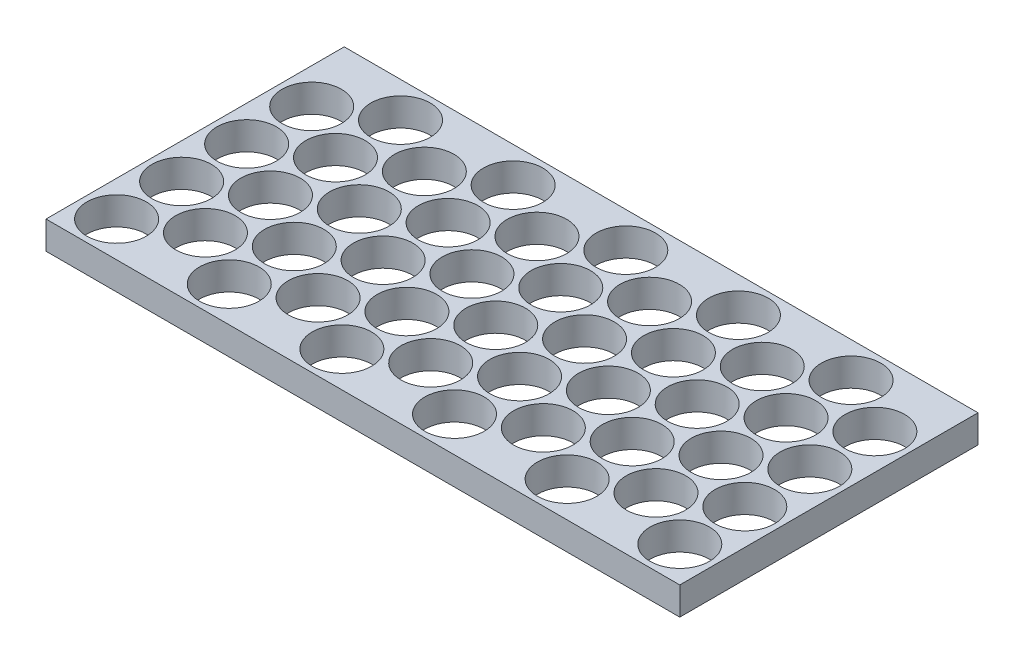
SolidWorks part; units mm, degrees
ref_plane "Front Plane" through (0, 0, 0) normal (0, 0, 1) x (1, 0, 0)
ref_plane "Top Plane" through (0, 0, 0) normal (0, 1, 0) x (1, 0, 0)
ref_plane "Right Plane" through (0, 0, 0) normal (1, 0, 0) x (0, 0, -1)
sketch "Sketch1" plane through (0, 0, 0) normal (0, 1, 0) x (1, 0, 0)
  line L1 (0, 0) -> (227.084, 0)
  line L2 (0, 0) -> (0, 106.85)
  line L3 (0, 106.85) -> (227.084, 106.85)
  line L4 (227.084, 0) -> (227.084, 106.85)
  dimension "D1" = 106.85
  dimension "D2" = 227.084
extrude "Boss-Extrude1" add sketch "Sketch1" along normal blind 10
ref_plane "Plane1" through (0, 0, -53.425) normal (0, 0, 1) x (1, 0, 0)
ref_plane "Plane2" through (113.542, 0, 0) normal (1, 0, 0) x (0, 0, -1)
sketch "Sketch5" plane through (0, 10, 0) normal (0, 1, 0) x (1, 0, 0)
  line L0 (113.542, -5.5) -> (113.542, 5.5) construction
  line L1 (-16.958, 4.075) -> (244.042, 4.075)
  line L2 (-16.958, 4.075) -> (-16.958, 102.775)
  line L3 (-16.958, 102.775) -> (244.042, 102.775)
  line L4 (244.042, 4.075) -> (244.042, 102.775)
  line L5 (-16.958, 4.075) -> (244.042, 102.775) construction
  line L6 (-16.958, 102.775) -> (244.042, 4.075) construction
  line L7 (-5.5, 53.425) -> (5.5, 53.425) construction
  point P0 (113.542, 53.425)
  dimension "D1" = 98.7
  dimension "D2" = 261
sketch "Sketch2" plane through (0, 10, 0) normal (0, 1, 0) x (1, 0, 0)
  line L0 (0, 0) -> (227.084, 0) construction
  line L1 (0, 106.85) -> (0, 0) construction
  circle A0 centre (12.65, 12.65) radius 10.65
  dimension "D1" = 21.3
  dimension "D2" = 12.65
  dimension "D3" = 12.65
extrude "Cut-Extrude1" cut sketch "Sketch2" against normal blind 22.3
pattern_linear "LPattern1" count 4 spacing 23.3 along (0, 0, -1) count 6 spacing 40.3568 along (1, 0, 0) of "Cut-Extrude1"
other "AdvancedHole1" [suppressed] parameters "D1"=10
sketch3d "3DSketch1"
  line L4 (267, 10, -96) -> (0, 10, -96) construction
  point P0 (251.75, 10, -91.25)
  point P2 (15.25, 10, -91.25)
  point P4 (90.5, 10, -91.25)
  point P6 (176.5, 10, -91.25)
  dimension "D1" = 118.25
  dimension "D3" = 4.75
  dimension "D2" = 43
sketch "Sketch3" plane through (251.75, 10, -91.25) normal (0, 0, -1) x (1, 0, 0)
  line L0 (0, 0) -> (0, 7.996)
  line L1 (0, -0.5) -> (0, 1.5) construction
  line L2 (2.97, 0) -> (2.64, 7.996)
  line L3 (-2.97, 0) -> (-2.64, 7.996) construction
  line L4 (0, 0) -> (2.97, 0)
  line L5 (2.64, 7.996) -> (0, 7.996)
  dimension "D1" = 7.996
  dimension "D2" = 5.94
  dimension "D3" = 4.727
mirror "Mirror1" [suppressed] about plane through (0, 0, -53.425) normal (0, 0, 1)
sketch "Sketch6" plane through (0, 10, 0) normal (0, 1, 0) x (1, 0, 0)
  line L0 (12.65, 35.95) -> (12.65, 12.65) construction
  circle A0 centre (32.8284, 24.3) radius 10.65
  point P2 (12.65, 24.3)
  dimension "D1" = 21.3
  dimension "D2" = 20.1784
extrude "Cut-Extrude2" cut sketch "Sketch6" against normal through all
pattern_linear "LPattern2" count 4 spacing 23.3 along (0, 0, -1) count 5 spacing 40.3568 along (1, 0, 0) of "Cut-Extrude2"
